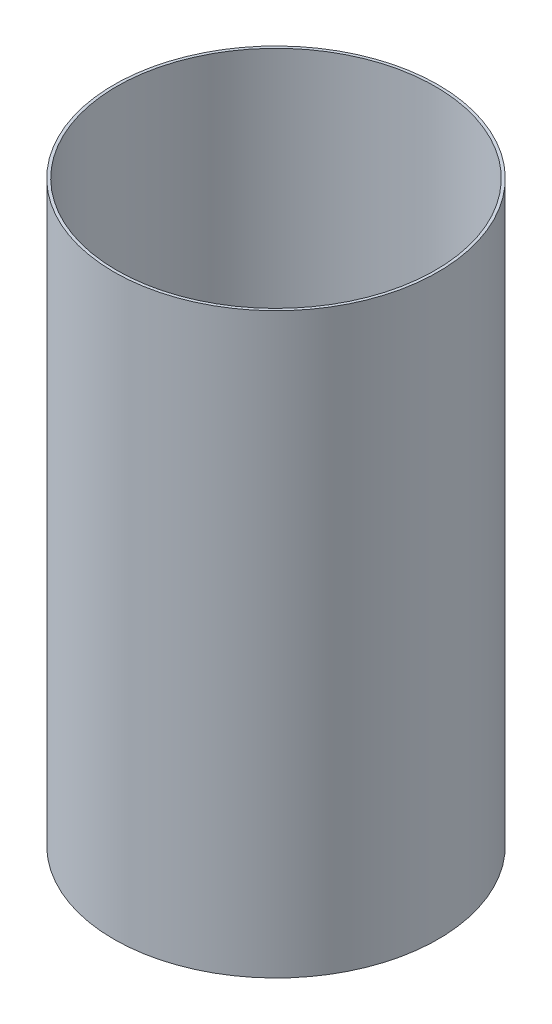
SolidWorks part; units mm, degrees
ref_plane "Front Plane" through (0, 0, 0) normal (0, 0, 1) x (1, 0, 0)
ref_plane "Top Plane" through (0, 0, 0) normal (0, 1, 0) x (1, 0, 0)
ref_plane "Right Plane" through (0, 0, 0) normal (1, 0, 0) x (0, 0, -1)
sketch "Sketch1" plane through (0, 0, 0) normal (0, 1, 0) x (1, 0, 0)
  circle A0 centre (0, 0) radius 64.135
  circle A1 centre (0, 0) radius 63.0174
  dimension "D1" = 128.27
  dimension "D2" = 1.1176
extrude "Boss-Extrude1" add sketch "Sketch1" along normal blind 228.6
